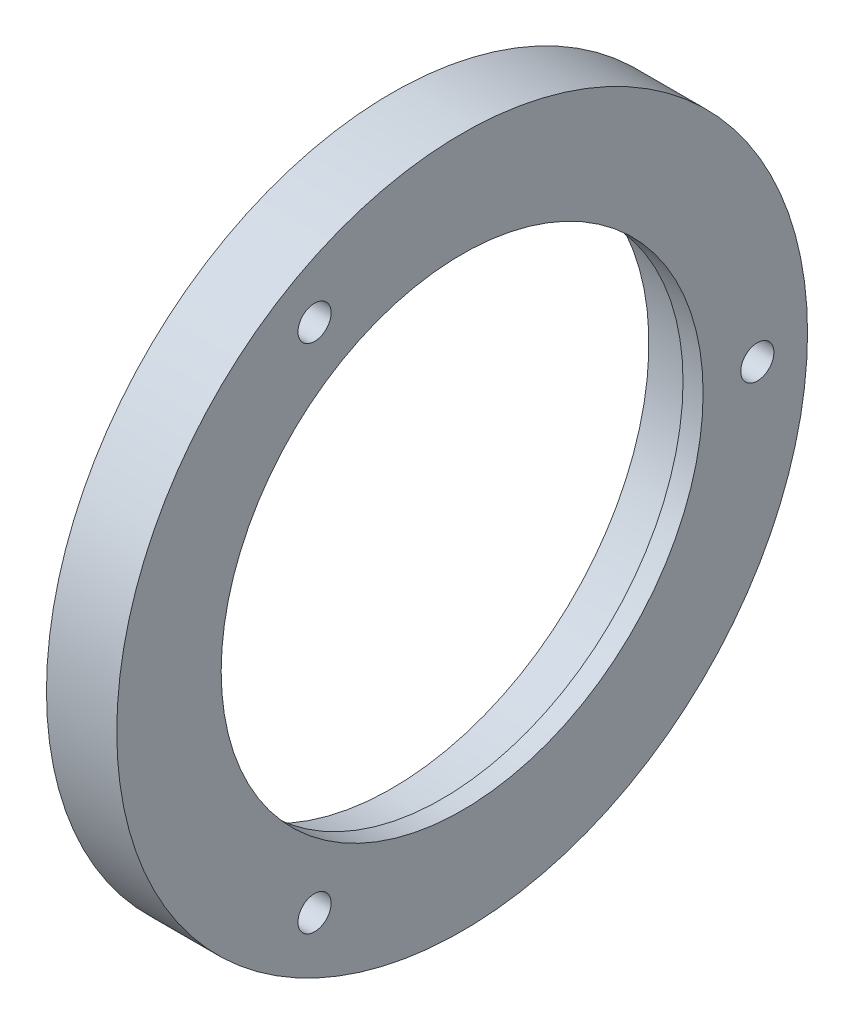
SolidWorks part; units mm, degrees
ref_plane "Front Plane" through (0, 0, 0) normal (0, 0, 1) x (1, 0, 0)
ref_plane "Top Plane" through (0, 0, 0) normal (0, 1, 0) x (1, 0, 0)
ref_plane "Right Plane" through (0, 0, 0) normal (1, 0, 0) x (0, 0, -1)
sketch "Axial profile (mm)" plane through (0, 0, 0) normal (0, 0, 1) x (1, 0, 0)
  line L0 (-110, 0) -> (75, 0) construction
  line L1 (169.7, 25.6) -> (174.7, 25.6)
  line L2 (174.7, 25.6) -> (174.7, 24)
  line L3 (174.7, 24) -> (176.7, 24)
  line L4 (176.7, 24) -> (176.7, 34.4)
  line L5 (176.7, 34.4) -> (169.7, 34.4)
  line L6 (169.7, 34.4) -> (169.7, 25.6)
revolve "Full revolution" add sketch "Axial profile (mm)" angle 360 about L0
sketch "Sketch2" plane through (0, 0, 0) normal (1, 0, 0) x (0, 0, -1)
  circle A0 centre (29.4, 0) radius 1.65
  circle A1 centre (-14.7, 25.4611) radius 1.65
  circle A2 centre (-14.7, -25.4611) radius 1.65
extrude "Axial holes" cut sketch "Sketch2" against normal through all and the other way through all
